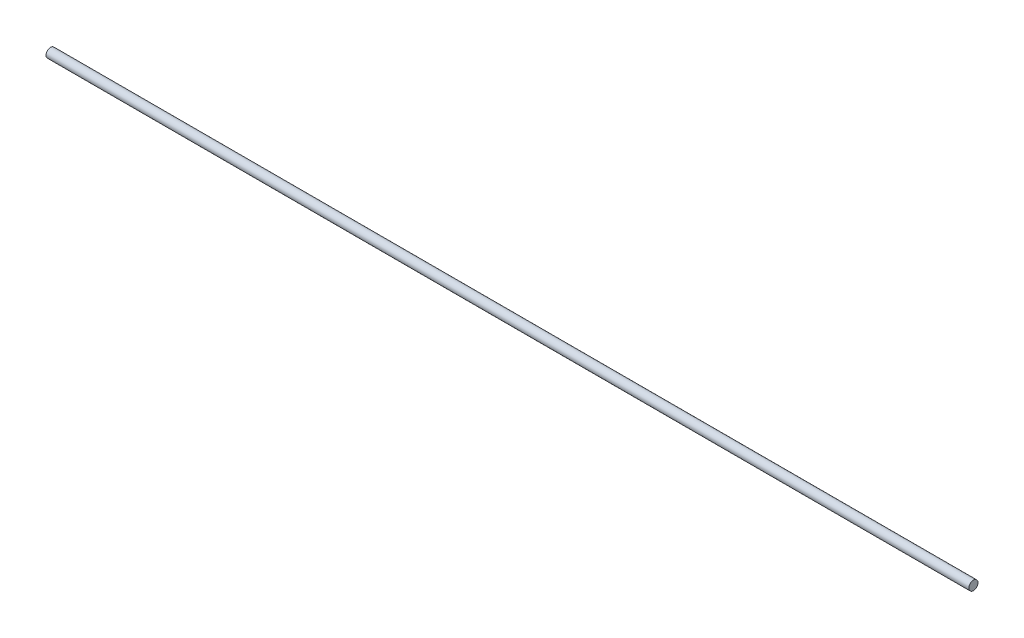
SolidWorks part; units mm, degrees
ref_plane "Front Plane" through (0, 0, 0) normal (0, 0, 1) x (1, 0, 0)
ref_plane "Top Plane" through (0, 0, 0) normal (0, 1, 0) x (1, 0, 0)
ref_plane "Right Plane" through (0, 0, 0) normal (1, 0, 0) x (0, 0, -1)
sketch "Sketch1" plane through (0, 0, 0) normal (1, 0, 0) x (0, 0, -1)
  circle A0 centre (0, 0) radius 3.9688
  dimension "D1" = 7.9375
extrude "Boss-Extrude1" add sketch "Sketch1" along normal offset from surface (800 mm away) 10
